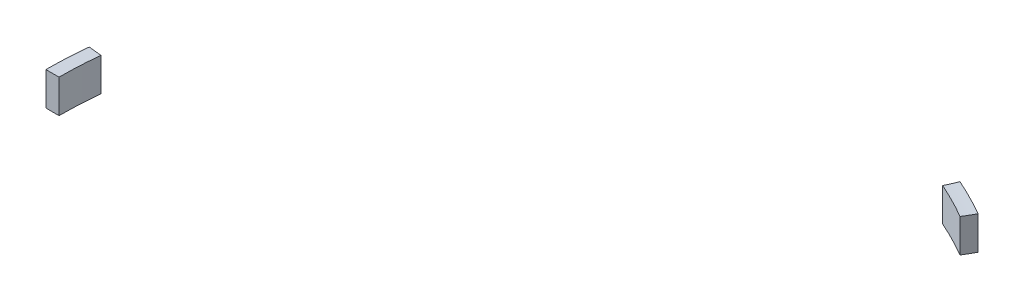
SolidWorks part; units mm, degrees
ref_plane "Front Plane" through (0, 0, 0) normal (0, 0, 1) x (1, 0, 0)
ref_plane "Top Plane" through (0, 0, 0) normal (0, 1, 0) x (1, 0, 0)
ref_plane "Right Plane" through (0, 0, 0) normal (1, 0, 0) x (0, 0, -1)
sketch "Sketch1" plane through (0, 0, 0) normal (0, 0, 1) x (1, 0, 0)
  line L2 (-0.5, -13.5508) -> (-0.5, -16.0972)
  line L3 (0.5, -13.5508) -> (0.5, -16.0972)
  arc A0 (-0.5, -16.0972) -> (0.5, -16.0972) centre (0, 0) ccw
  arc A2 (-0.5, -13.5508) -> (0.5, -13.5508) centre (0, 0) ccw
  dimension "D1" = 32.21
sketch "Sketch2" plane through (0, 0, 0) normal (0, 1, 0) x (1, 0, 0)
  line L0 (0, 0) -> (29.53, 0) construction
  line L1 (29.53, 0) -> (44.295, 25.5737) construction
  arc A1 (44.295, 25.5737) -> (0, 0) centre (29.53, 0) ccw
  point P3 (0, 0)
  point P4 (44.295, 25.5737)
  dimension "D1" = 29.53
  dimension "D2" = 120
sweep "Sweep1" add profiles "Sketch1" path "Sketch2"
sketch "Sketch3" plane through (0, 0, 0) normal (0, 1, 0) x (1, 0, 0)
  line L0 (29.53, 0) -> (41.7443, 27.4338)
  line L1 (44.545, 26.0067) -> (44.045, 25.1407)
  line L3 (0.5, 0) -> (-0.5, 0)
  line L4 (29.53, 0) -> (-0.3355, 3.139)
  arc A2 (44.045, 25.1407) -> (0.5, 0) centre (29.53, 0) ccw
  arc A3 (44.545, 26.0067) -> (-0.5, 0) centre (29.53, 0) ccw
  dimension "D1" = 6
  dimension "D2" = 6
extrude "Cut-Extrude2" cut sketch "Sketch3" against normal blind 20 contours L0 A3 L4 A2
